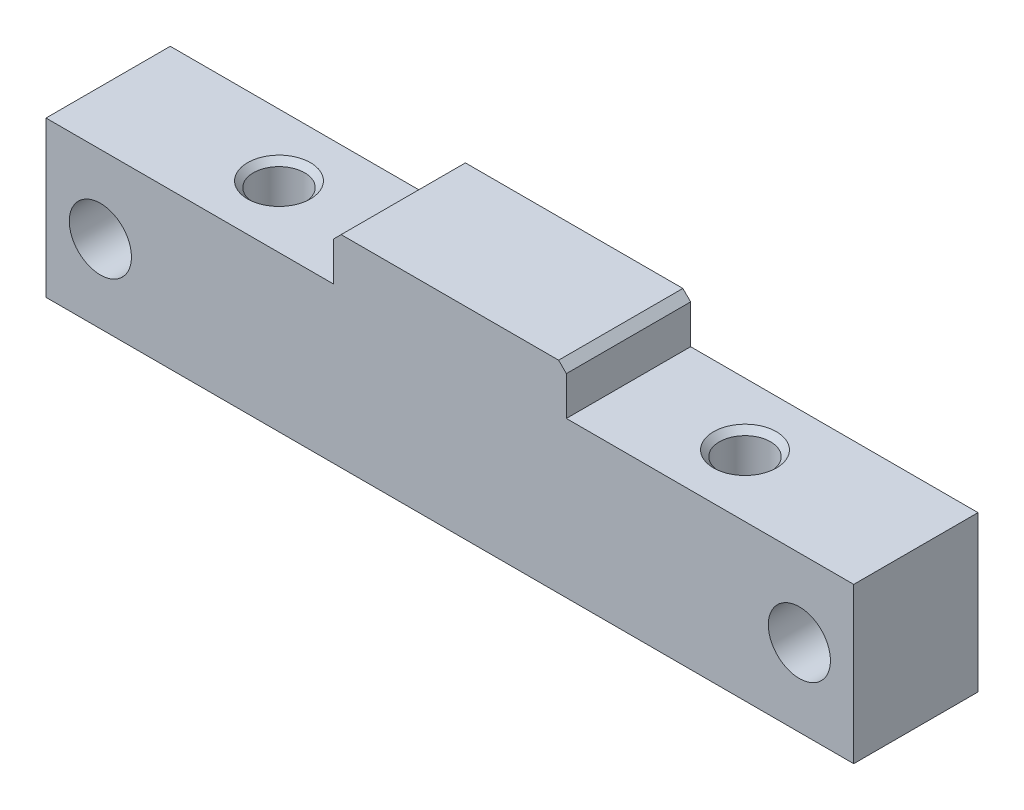
SolidWorks part; units mm, degrees
material "6061 合金"
ref_plane "前视基准面" through (0, 0, 0) normal (0, 0, 1) x (1, 0, 0)
ref_plane "上视基准面" through (0, 0, 0) normal (0, 1, 0) x (1, 0, 0)
ref_plane "右视基准面" through (0, 0, 0) normal (1, 0, 0) x (0, 0, -1)
sketch "草图2" plane through (0, 0, 0) normal (0, 0, 1) x (1, 0, 0)
  line L0 (0, 51.8525) -> (0, -73.6934) construction
  line L1 (-7.5, 13) -> (7.5, 13)
  line L2 (7.5, 13) -> (7.5, 10)
  line L3 (7.5, 10) -> (26, 10)
  line L4 (26, 10) -> (26, 0)
  line L5 (26, 0) -> (-26, 0)
  line L6 (-26, 10) -> (-26, 0)
  line L7 (-7.5, 10) -> (-26, 10)
  line L8 (-7.5, 13) -> (-7.5, 10)
  point P9 (4.0643, 10)
  point P11 (0, 0)
  point P14 (0, 13)
  dimension "D1" = 10
  dimension "D2" = 3
  dimension "D3" = 52
  dimension "D4" = 15
extrude "凸台-拉伸1" add sketch "草图2" along normal blind 8
sketch "草图4" plane through (0, 0, 8) normal (0, 0, 1) x (1, 0, 0)
  line L0 (0, 21.0474) -> (0, -12.7895) construction
  line L1 (26, 5) -> (-22.5, 5) construction
  line L3 (-26, 0) -> (26, 0) construction
  circle A0 centre (-22.5, 5) radius 2
  circle A1 centre (22.5, 5) radius 2
  dimension "D1" = 45
  dimension "D2" = 4
  dimension "D3" = 5
extrude "切除-拉伸3" cut sketch "草图4" against normal through all
sketch "草图5" plane through (0, 10, 0) normal (0, 1, 0) x (1, 0, 0)
  line L0 (-26, -4) -> (26, -4) construction
  line L1 (-26, -8) -> (-26, 0) construction
  line L2 (26, -8) -> (26, 0) construction
  line L3 (0, 8.3299) -> (0, -19.0439) construction
  point P6 (-15, -4)
  point P7 (15, -4)
  point P11 (0, 0)
  dimension "D1" = 30
hole_wizard "M4 螺纹孔1" positions "3D草图1" profile "草图6" tap size "M4" standard "GB"
sketch3d "3D草图1"
  point P0 (-15, 10, 4)
  point P2 (15, 10, 4)
  point P5 (-16, 10, 3)
  point P7 (16, 10, 3)
cosmetic thread "孔螺蚊线1" parameters "D1"=10, "D2"=4
cosmetic thread "孔螺蚊线2" parameters "D1"=10, "D2"=4
sketch "草图6" plane through (-15, 10, 4) normal (1, 0, 0) x (0, 0, 1)
  line L0 (0, 0) -> (0, 10.9914)
  line L1 (0, 10.9914) -> (1.65, 10)
  line L2 (1.65, 10) -> (1.65, 0.375)
  line L3 (1.65, 0.375) -> (2.025, 0)
  line L5 (2.025, 0) -> (0, 0)
  line L6 (-1.65, 0.375) -> (-2.025, 0) construction
  line L10 (0, 10.9914) -> (-1.65, 10) construction
  line L11 (0, -6.35) -> (0, 107.95) construction
  dimension "螺纹孔钻头直径" = 3.3
  dimension "螺纹孔钻头深度" = 10
  dimension "近端锥形沉头孔直径" = 4.05
  dimension "近端锥形沉头孔角度" = 90
  dimension "导头角度" = 118
chamfer "倒角1" distance 0.5 angle 45 2 edges at (7.5, 13, 4) (-7.5, 13, 4)
